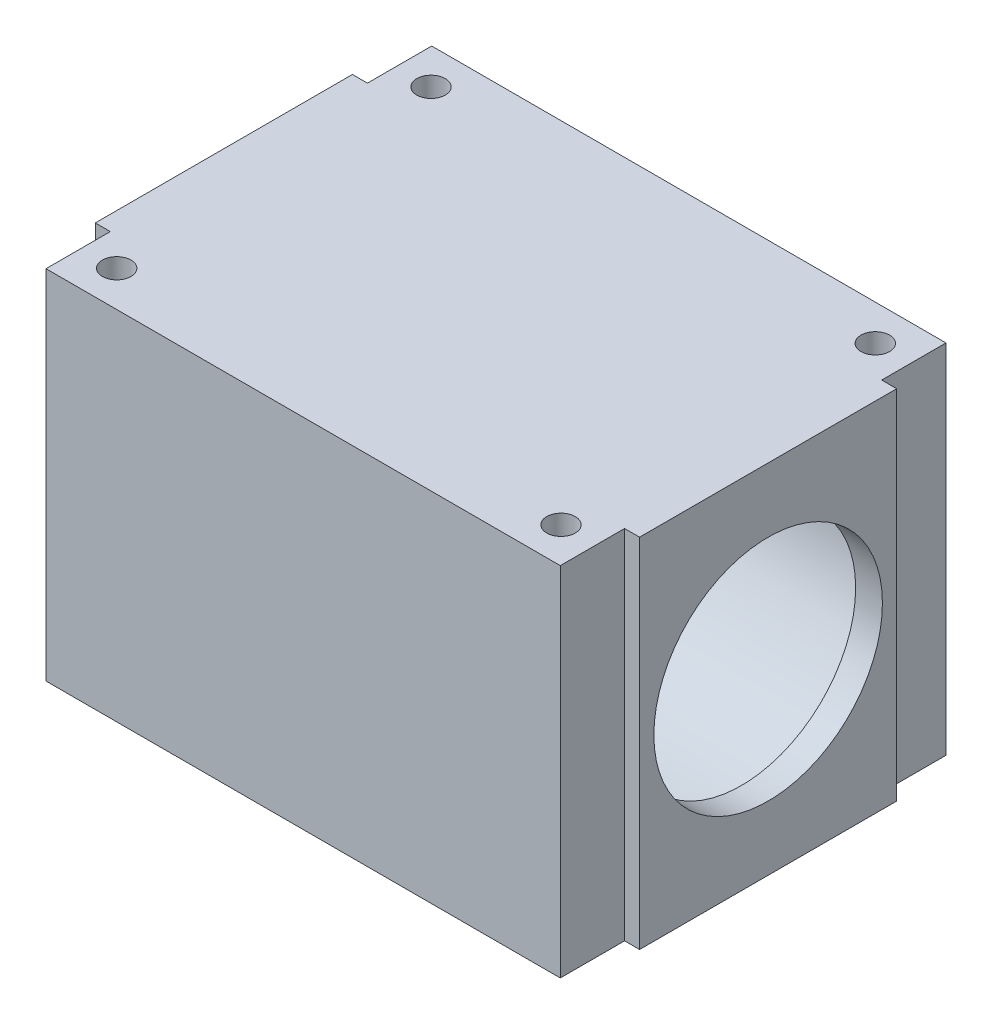
SolidWorks part; units mm, degrees
ref_plane "Front Plane" through (0, 0, 0) normal (0, 0, 1) x (1, 0, 0)
ref_plane "Top Plane" through (0, 0, 0) normal (0, 1, 0) x (1, 0, 0)
ref_plane "Right Plane" through (0, 0, 0) normal (1, 0, 0) x (0, 0, -1)
sketch "Sketch1" plane through (0, 0, 0) normal (1, 0, 0) x (0, 0, -1)
  line L1 (-27, -25) -> (27, -25)
  line L2 (-27, -25) -> (-27, 25)
  line L3 (-27, 25) -> (27, 25)
  line L4 (27, -25) -> (27, 25)
  line L5 (-27, -25) -> (27, 25) construction
  line L6 (-27, 25) -> (27, -25) construction
  circle A0 centre (0, 0) radius 23.9
  point P0 (0, 0)
  dimension "D2" = 47.8
  dimension "D1" = 54
  dimension "D3" = 50
extrude "Boss-Extrude1" add sketch "Sketch1" along normal blind 68.2
sketch "Sketch2" plane through (68.2, 0, 0) normal (1, 0, 0) x (0, 0, -1)
  line L1 (-27, -25) -> (27, -25)
  line L2 (-27, -25) -> (-27, 25)
  line L3 (-27, 25) -> (27, 25)
  line L4 (27, -25) -> (27, 25)
  line L5 (-27, -25) -> (27, 25) construction
  line L6 (-27, 25) -> (27, -25) construction
  circle A0 centre (0, 0) radius 16
  point P0 (0, 0)
  dimension "D1" = 32
extrude "Boss-Extrude2" add sketch "Sketch2" along normal blind 2
pattern_linear "LPattern1" count 2 spacing 70.2 along (-1, 0, 0) of "Boss-Extrude2"
sketch "Sketch3" plane through (0, -25, 0) normal (0, -1, 0) x (1, 0, 0)
  line L0 (70.2, 27) -> (-2, 27) construction
  line L1 (-2, 27) -> (-2, -27) construction
  line L2 (70.2, 27) -> (70.2, -27) construction
  line L3 (70.2, -27) -> (-2, -27) construction
  line L4 (3, 24) -> (8.4012, 24) construction
  line L5 (-2, 0) -> (70.2, 0) construction
  circle A0 centre (3, 22) radius 2
  circle A1 centre (65.2, 22) radius 2
  circle A2 centre (65.2, -22) radius 2
  circle A3 centre (3, -22) radius 2
  dimension "D1" = 4
  dimension "D2" = 5
  dimension "D3" = 5
  dimension "D4" = 5
  dimension "D5" = 5
  dimension "D6" = 5
  dimension "D7" = 5
  dimension "D8" = 5
  dimension "D9" = 5
  dimension "D10" = 3
  dimension "D11" = 72.2
extrude "Cut-Extrude1" cut sketch "Sketch3" against normal blind 7
mirror "Mirror1" about plane through (0, 0, 0) normal (0, 1, 0) of "Cut-Extrude1"
sketch "Sketch6" plane through (70.2, 0, 0) normal (1, 0, 0) x (0, 0, -1)
  line L1 (-27, -25) -> (27, -25)
  line L2 (-27, -25) -> (-27, 25)
  line L3 (-27, 25) -> (27, 25)
  line L4 (27, -25) -> (27, 25)
  line L5 (-27, -25) -> (27, 25) construction
  line L6 (-27, 25) -> (27, -25) construction
  circle A0 centre (0, 0) radius 16
sketch "Sketch7" plane through (-2, 0, 0) normal (-1, 0, 0) x (0, 0, 1)
  line L1 (-27, -25) -> (27, -25)
  line L2 (-27, -25) -> (-27, 25)
  line L3 (-27, 25) -> (27, 25)
  line L4 (27, -25) -> (27, 25)
  line L5 (-27, -25) -> (27, 25) construction
  line L6 (-27, 25) -> (27, -25) construction
  circle A0 centre (0, 0) radius 16
extrude "Boss-Extrude5" add sketch "Sketch7" along normal blind 2
extrude "Boss-Extrude6" add sketch "Sketch6" along normal blind 2
sketch "Sketch8" plane through (68.2, 0, 0) normal (-1, 0, 0) x (0, 0, 1)
  circle A0 centre (0, 0) radius 23.9
extrude "Cut-Extrude2" cut sketch "Sketch8" against normal blind 0.25
sketch "Sketch9" plane through (0, 0, 0) normal (1, 0, 0) x (0, 0, -1)
  circle A0 centre (0, 0) radius 23.9
extrude "Cut-Extrude3" cut sketch "Sketch9" against normal blind 0.25
sketch "Sketch10" plane through (72.2, 0, 0) normal (1, 0, 0) x (0, 0, -1)
  line L0 (-27, -25) -> (27, -25) construction
  line L1 (-27, 25) -> (-18, 25)
  line L2 (-27, 25) -> (-27, -25)
  line L3 (-27, -25) -> (-18, -25)
  line L4 (-18, 25) -> (-18, -25)
  line L6 (27, 25) -> (18, 25)
  line L7 (27, 25) -> (27, -25)
  line L8 (27, -25) -> (18, -25)
  line L9 (18, 25) -> (18, -25)
  dimension "D1" = 9
  dimension "D2" = 9
extrude "Cut-Extrude4" cut sketch "Sketch10" against normal blind 2.1
sketch "Sketch11" plane through (-4, 0, 0) normal (-1, 0, 0) x (0, 0, 1)
  line L0 (27, 25) -> (-27, 25) construction
  line L1 (-27, -25) -> (-18, -25)
  line L2 (-27, -25) -> (-27, 25)
  line L3 (-27, 25) -> (-18, 25)
  line L4 (-18, -25) -> (-18, 25)
  line L5 (27, -25) -> (18, -25)
  line L6 (27, -25) -> (27, 25)
  line L7 (27, 25) -> (18, 25)
  line L8 (18, -25) -> (18, 25)
  dimension "D1" = 9
  dimension "D2" = 9
extrude "Cut-Extrude5" cut sketch "Sketch11" against normal blind 2.1
